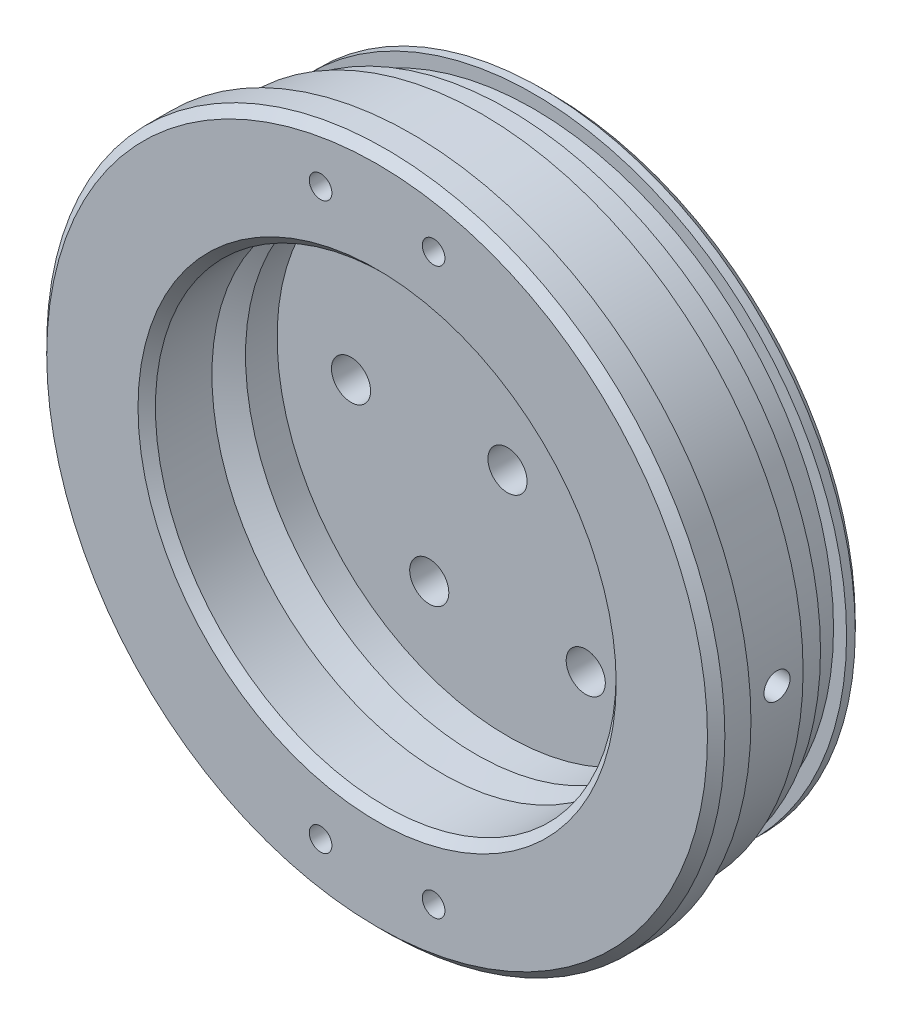
SolidWorks part; units mm, degrees
ref_plane "Спереди" through (0, 0, 0) normal (0, 0, 1) x (1, 0, 0)
ref_plane "Сверху" through (0, 0, 0) normal (0, 1, 0) x (1, 0, 0)
ref_plane "Справа" through (0, 0, 0) normal (1, 0, 0) x (0, 0, -1)
sketch "Эскиз1" plane through (0, 0, 0) normal (0, 0, 1) x (1, 0, 0)
  circle A0 centre (0, 0) radius 39
  dimension "D1" = 78
extrude "Бобышка-Вытянуть1" add sketch "Эскиз1" along normal blind 4
sketch "Эскиз2" plane through (0, 0, 4) normal (0, 0, 1) x (1, 0, 0)
  line L0 (0, 40.548) -> (0, -43.3588) construction
sketch "Эскиз3" plane through (0, 0, 0) normal (0, 0, -1) x (-1, 0, 0)
  circle A0 centre (0, 0) radius 37
  dimension "D1" = 74
extrude "Бобышка-Вытянуть2" add sketch "Эскиз3" along normal blind 8
sketch "Эскиз4" plane through (0, 0, -8) normal (0, 0, -1) x (-1, 0, 0)
  circle A0 centre (0, 0) radius 36
  dimension "D1" = 72
extrude "Бобышка-Вытянуть3" add sketch "Эскиз4" along normal blind 8
sketch "Эскиз5" plane through (0, 0, 0) normal (1, 0, 0) x (0, 0, -1)
  line L0 (-46.651, 0) -> (48.0815, 0) construction
  line L1 (16, 36) -> (8, 36) construction
  line L2 (14, 36) -> (11, 36)
  line L3 (14, 36) -> (14, 34.5)
  line L4 (14, 34.5) -> (11, 34.5)
  line L5 (11, 36) -> (11, 34.5)
  line L6 (16, -36) -> (16, 36) construction
  dimension "D1" = 2
  dimension "D2" = 1.5
  dimension "D3" = 3
revolve "Вырез-Повернуть1" cut sketch "Эскиз5" angle 360 about L0
sketch "Эскиз7" plane through (0, 0, -16) normal (0, 0, -1) x (-1, 0, 0)
  circle A0 centre (0, 0) radius 27
  dimension "D1" = 54
extrude "Вырез-Вытянуть1" cut sketch "Эскиз7" against normal blind 17
chamfer "Фаска2" distance 1 angle 45 1 edges at (-36, 0, -16)
ref_plane "Плоскость6" [suppressed] through (37, 0, 0) normal (1, 0, 0) x (0, 0, -1)
sketch "Эскиз14" [suppressed] plane through (37, 0, 0) normal (1, 0, 0) x (0, 0, -1)
  line L0 (0, 0) -> (8.9796, 0) construction
  line L1 (8, -37) -> (8, 37) construction
  circle A0 centre (5, 0) radius 1.3
  dimension "D2" = 2.6
  dimension "D1" = 3
extrude "Вырез-Вытянуть4" [suppressed] cut sketch "Эскиз14" against normal blind 7
ref_plane "Плоскость7" [suppressed] through (-37, 0, 0) normal (1, 0, 0) x (0, 0, -1)
sketch "Эскиз16" [suppressed] plane through (-37, 0, 0) normal (1, 0, 0) x (0, 0, -1)
  line L0 (0, 0) -> (13.6916, 0) construction
  line L1 (8, -36) -> (8, 36) construction
  circle A0 centre (5, 0) radius 1.3
  dimension "D2" = 2.6
  dimension "D1" = 3
extrude "Вырез-Вытянуть5" [suppressed] cut sketch "Эскиз16" along normal blind 7
thread "Резьба1" [suppressed] pitch 0.3 start angle 0, offset 0, length 7, pitch 0.3, diameter 2.6
ref_plane "Плоскость8" through (37, 0, -3.7) normal (0, -1, 0) x (0, 0, 1)
sketch "Профиль резьбы1" plane through (37, 0, -3.7) normal (0, -1, 0) x (0, 0, 1)
  line L0 (0, 0) -> (0, 0.3) construction
  line L11 (0, 0.2625) -> (0, 0)
  line L12 (0, 0) -> (0.1624, 0.0938)
  line L13 (0.1624, 0.0938) -> (0.1624, 0.1688)
  line L15 (0.1624, 0.1688) -> (0, 0.2625)
  line L17 (0.1624, 0.1313) -> (0, 0.1313) construction
  point P3 (0, 0)
  dimension "Pitch" = 0.3
  dimension "Profile_Angle" = 60
  dimension "Profile_Land" = 0.075
  dimension "Profile_Height" = 0.1624
thread "Резьба2" [suppressed] pitch 0.3 start angle 0, offset 0, length 7, pitch 0.3, diameter 2.6
ref_plane "Плоскость9" through (-37, 0, -6.3) normal (0, -1, 0) x (0, 0, -1)
sketch "Профиль резьбы2" plane through (-37, 0, -6.3) normal (0, -1, 0) x (0, 0, -1)
  line L0 (0, 0) -> (0, 0.3) construction
  line L11 (0, 0.2625) -> (0, 0)
  line L12 (0, 0) -> (0.1624, 0.0938)
  line L13 (0.1624, 0.0938) -> (0.1624, 0.1688)
  line L15 (0.1624, 0.1688) -> (0, 0.2625)
  line L17 (0.1624, 0.1313) -> (0, 0.1313) construction
  point P3 (0, 0)
  dimension "Pitch" = 0.3
  dimension "Profile_Angle" = 60
  dimension "Profile_Land" = 0.075
  dimension "Profile_Height" = 0.1624
sketch "Эскиз18" plane through (0, 0, 4) normal (0, 0, 1) x (1, 0, 0)
  line L0 (0, 32.5) -> (12.4261, 32.5) construction
  line L1 (0, 46.4307) -> (0, -52.0425) construction
  line L2 (-51.6992, 0) -> (67.4175, 0) construction
  circle A0 centre (6.5, 32.5) radius 1.3
  circle A1 centre (-6.5, 32.5) radius 1.3
  circle A2 centre (6.5, -32.5) radius 1.3
  circle A3 centre (-6.5, -32.5) radius 1.3
  dimension "D1" = 2.6
  dimension "D2" = 6.5
extrude "Вырез-Вытянуть6" cut sketch "Эскиз18" against normal blind 7
sketch "Эскиз19" plane through (0, 0, 1) normal (0, 0, -1) x (-1, 0, 0)
  circle A0 centre (0, 0) radius 27
extrude "Бобышка-Вытянуть4" add sketch "Эскиз19" along normal blind 17
sketch "Эскиз20" plane through (0, 0, 4) normal (0, 0, 1) x (1, 0, 0)
  circle A0 centre (0, 0) radius 26.5
  dimension "D1" = 53
extrude "Вырез-Вытянуть7" cut sketch "Эскиз20" against normal blind 15
sketch "Эскиз21" plane through (0, 0, -11) normal (0, 0, 1) x (1, 0, 0)
  circle A1 centre (-18, 0) radius 2.25
  circle A2 centre (-9, 15.5885) radius 2.25
  circle A3 centre (9, 15.5885) radius 2.25
  circle A4 centre (18, 0) radius 2.25
  circle A5 centre (9, -15.5885) radius 2.25
  circle A6 centre (-9, -15.5885) radius 2.25
  circle A7 centre (0, 0) radius 2.25
  point P20 (0, 0)
  dimension "D2" = 4.5
  dimension "D4" = 4.5
  dimension "D3" = 6
extrude "Вырез-Вытянуть8" cut sketch "Эскиз21" against normal blind 15
sketch "Эскиз22" plane through (0, 0, 0) normal (1, 0, 0) x (0, 0, -1)
  line L0 (-32.0056, 0) -> (47.7052, 0) construction
  line L1 (3.5, 26.5) -> (5.3834, 29.8175)
  line L2 (11, 26.5) -> (-4, 26.5) construction
  line L3 (5.3834, 29.8175) -> (7.3635, 26.5)
  line L4 (7.3635, 26.5) -> (3.5, 26.5)
revolve "Вырез-Повернуть2" cut sketch "Эскиз22" angle 360 about L0
sketch "Эскиз23" plane through (0, 0, -16) normal (0, 0, -1) x (-1, 0, 0)
  line L0 (0, 0) -> (-47.0865, 0) construction
  line L1 (0, 40.548) -> (0, -5.6095) construction
  line L2 (0, 40.548) -> (0, -43.3588) construction
  line L3 (-15.8507, 22.0606) -> (23.6591, 22.0606) construction
  circle A2 centre (23.1804, 22.0606) radius 1.3
  circle A3 centre (-23.1804, 22.0606) radius 1.3
  circle A4 centre (23.1804, -22.0606) radius 1.3
  circle A5 centre (-23.1804, -22.0606) radius 1.3
  point P13 (0, 36.0606)
  dimension "D2" = 14
  dimension "D3" = 2.6
extrude "Вырез-Вытянуть9" cut sketch "Эскиз23" against normal blind 7
sketch "Эскиз25" plane through (0, 0, 0) normal (1, 0, 0) x (0, 0, -1)
  line L0 (0, 0) -> (50000, 0) construction
  line L1 (0, -39) -> (0, 39) construction
  circle A0 centre (5, 0) radius 1.5
  dimension "D1" = 3
  dimension "D2" = 5
extrude "Вырез-Вытянуть11" cut sketch "Эскиз25" against normal blind 4 from offset 38
pattern_circular "Круговой массив2" count 2 over 360 about axis through (0, 0, -8) along (0, 0, 1) of "Вырез-Вытянуть11"
chamfer "Фаска3" distance 1 angle 45 2 edges at (26.5, 0, 4) (39, 0, 4)
